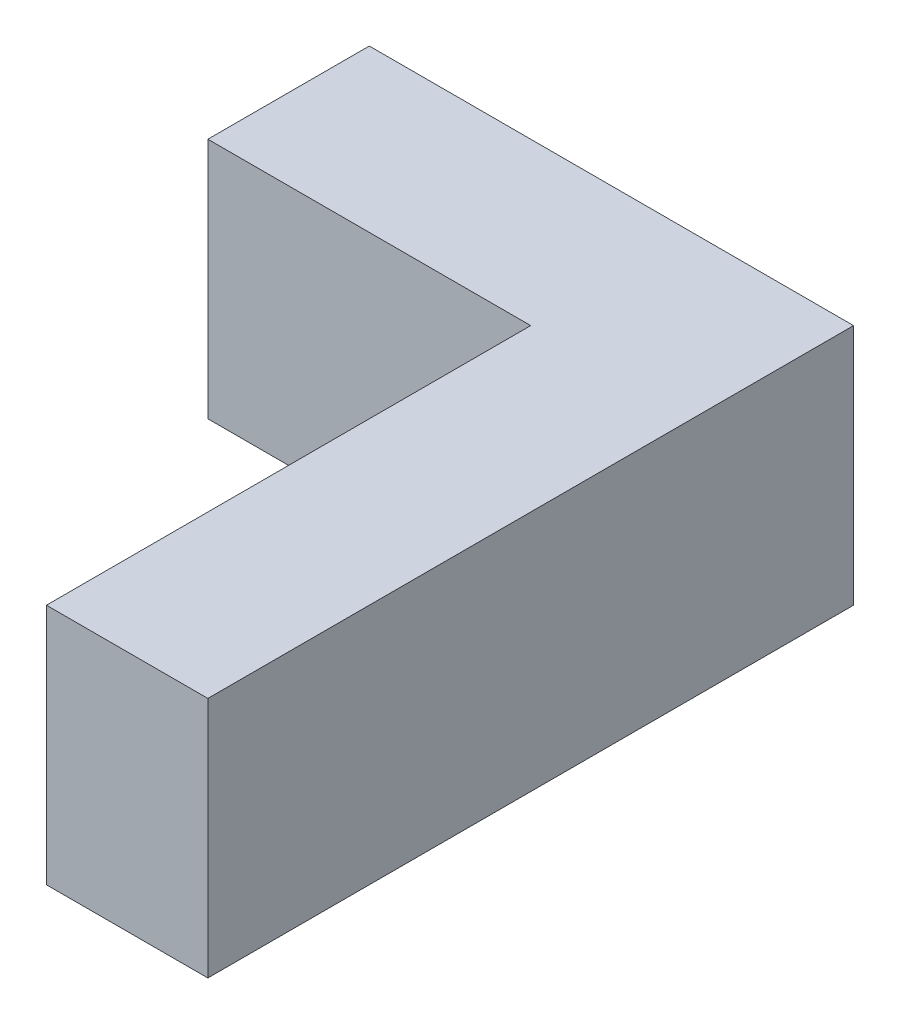
SolidWorks part; units mm, degrees
material "NON SPECIFIE"
ref_plane "Plan de face" through (0, 0, 0) normal (0, 0, 1) x (1, 0, 0)
ref_plane "Plan de dessus" through (0, 0, 0) normal (0, 1, 0) x (1, 0, 0)
ref_plane "Plan de droite" through (0, 0, 0) normal (1, 0, 0) x (0, 0, -1)
sketch "Sketch1" plane through (0, 0, 0) normal (0, 1, 0) x (1, 0, 0)
  line L0 (-15, -20) -> (15, 20) construction
  line L1 (-15, -20) -> (15, -20)
  line L2 (-15, -20) -> (-15, 20)
  line L3 (-15, 20) -> (15, 20)
  line L4 (15, -20) -> (15, 20)
  point P4 (0, 0)
  dimension "D1" = 40
  dimension "D2" = 30
extrude "Boss-Extrude1" add sketch "Sketch1" along normal blind 15
sketch "Sketch2" plane through (0, 15, 0) normal (0, 1, 0) x (1, 0, 0)
  line L0 (15, 20) -> (-15, 20) construction
  line L1 (-15, -20) -> (5, -20)
  line L2 (-15, -20) -> (-15, 10)
  line L3 (-15, 10) -> (5, 10)
  line L4 (5, -20) -> (5, 10)
  line L5 (15, -20) -> (15, 20) construction
  dimension "D1" = 10
  dimension "D2" = 10
extrude "Cut-Extrude1" cut sketch "Sketch2" against normal up to next
